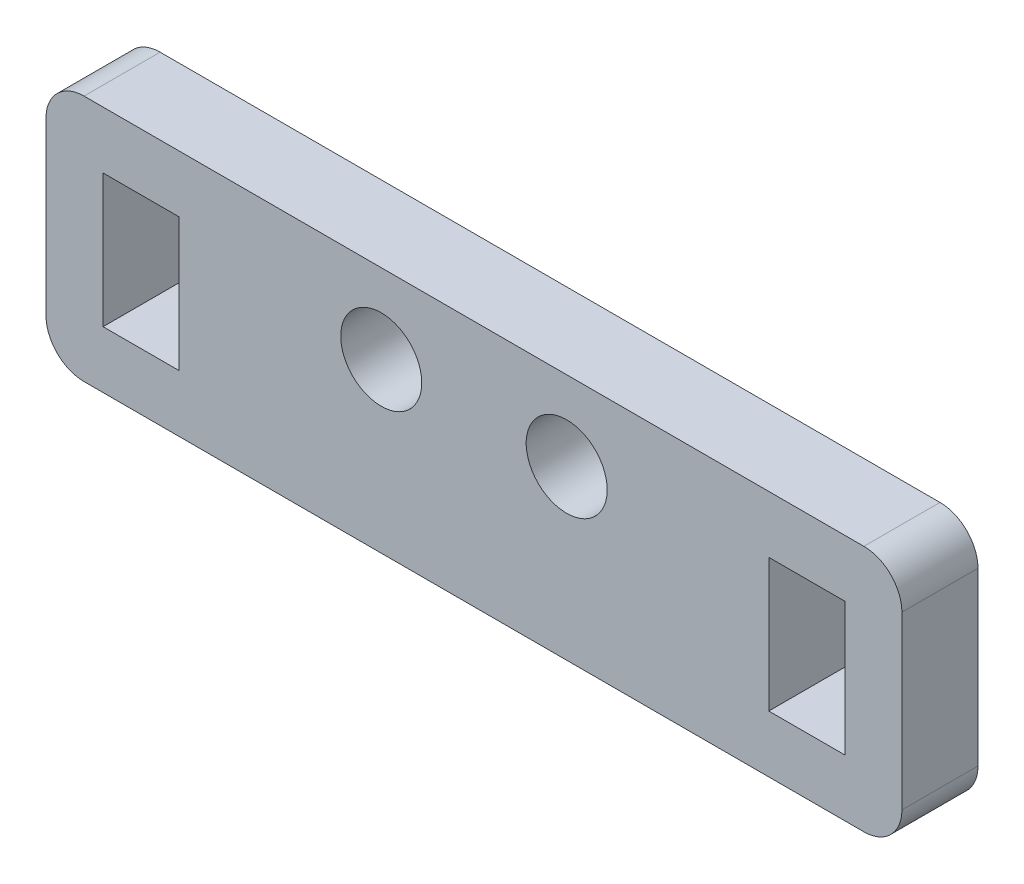
SolidWorks part; units mm, degrees
ref_plane "Plan de face" through (0, 0, 0) normal (0, 0, 1) x (1, 0, 0)
ref_plane "Plan de dessus" through (0, 0, 0) normal (0, 1, 0) x (1, 0, 0)
ref_plane "Plan de droite" through (0, 0, 0) normal (1, 0, 0) x (0, 0, -1)
sketch "Esquisse1" plane through (0, 0, 0) normal (0, 0, 1) x (1, 0, 0)
  line L0 (-22.5, 6.5) -> (22.5, -6.5) construction
  line L5 (-22.5, -6.5) -> (22.5, -6.5)
  line L6 (-22.5, -6.5) -> (-22.5, 6.5)
  line L7 (-19.5, 3.5) -> (-15.5, 3.5)
  line L8 (-19.5, 3.5) -> (-19.5, -3.5)
  line L9 (-19.5, -3.5) -> (-15.5, -3.5)
  line L10 (-15.5, 3.5) -> (-15.5, -3.5)
  line L11 (15.5, 3.5) -> (19.5, 3.5)
  line L12 (15.5, 3.5) -> (15.5, -3.5)
  line L13 (15.5, -3.5) -> (19.5, -3.5)
  line L14 (19.5, 3.5) -> (19.5, -3.5)
  line L15 (-22.5, 6.5) -> (22.5, 6.5)
  line L16 (0, -13.5667) -> (0, 14.4333) construction
  line L17 (22.5, -6.5) -> (22.5, 6.5)
  line L18 (22.5, 6.5) -> (-22.5, -6.5) construction
  line L19 (-22.4543, 0) -> (32.8124, 0) construction
  line L20 (-19.5, 3.5) -> (-19.5, 6.5) construction
  line L21 (-19.5, 3.5) -> (-22.5, 3.5) construction
  circle A0 centre (-4.875, 2.32) radius 2.13
  circle A1 centre (4.875, 2.32) radius 2.13
  point P0 (0, 0)
  dimension "D3" = 4.26
  dimension "D1" = 4
  dimension "D2" = 7
  dimension "D4" = 4.18
  dimension "D5" = 9.75
  dimension "D6" = 3
  dimension "D7" = 45
extrude "Boss.-Extru.1" add sketch "Esquisse1" along normal blind 4
fillet "Congé1" radius 2 4 edges at (22.5, -6.5, 2) (22.5, 6.5, 2) (-22.5, -6.5, 2) (-22.5, 6.5, 2)
